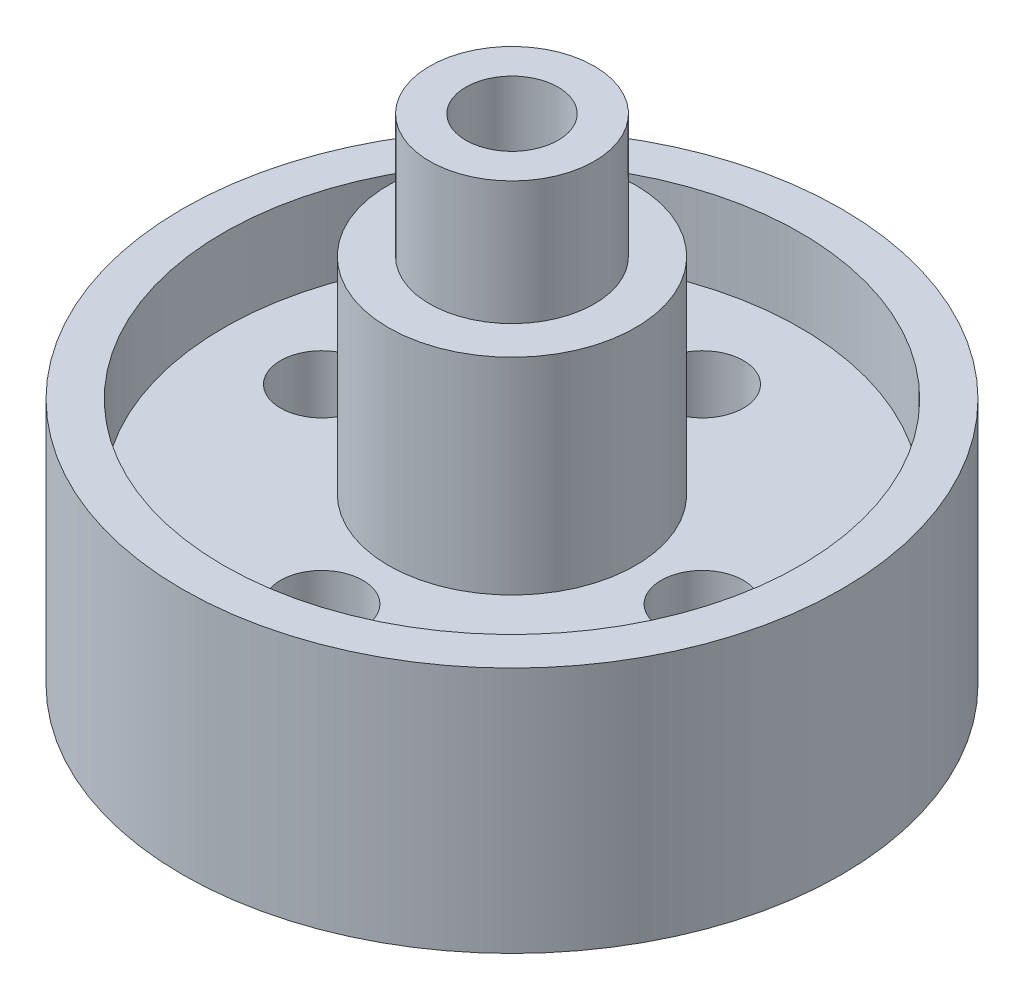
SolidWorks part; units mm, degrees
ref_plane "Front Plane" through (0, 0, 0) normal (0, 0, 1) x (1, 0, 0)
ref_plane "Top Plane" through (0, 0, 0) normal (0, 1, 0) x (1, 0, 0)
ref_plane "Right Plane" through (0, 0, 0) normal (1, 0, 0) x (0, 0, -1)
sketch "Sketch1" plane through (0, 0, 0) normal (0, 1, 0) x (1, 0, 0)
  circle A0 centre (0, 0) radius 50.8
  dimension "D1" = 101.6
extrude "Boss-Extrude1" add sketch "Sketch1" along normal blind 25.4
sketch "Sketch2" plane through (0, 25.4, 0) normal (0, 1, 0) x (1, 0, 0)
  circle A0 centre (-29.337, 0) radius 6.35
  circle A1 centre (0, 29.337) radius 6.35
  circle A2 centre (29.337, 0) radius 6.35
  circle A3 centre (0, -29.337) radius 6.35
  point P12 (0, 0)
  dimension "D1" = 12.7
  dimension "D2" = 29.337
  dimension "D3" = 4
extrude "Cut-Extrude1" cut sketch "Sketch2" against normal blind 25.4
sketch "Sketch3" plane through (0, 25.4, 0) normal (0, 1, 0) x (1, 0, 0)
  circle A0 centre (0, 0) radius 19.05
  circle A1 centre (0, 0) radius 44.45
  circle A2 centre (0, 0) radius 50.8
  circle M5 centre (0, 0) radius 50.8
  dimension "D1" = 88.9
  dimension "D2" = 38.1
  dimension "D3" = 6.35
extrude "Boss-Extrude2" add sketch "Sketch3" along normal blind 12.7 contours A1 M5
sketch "Sketch5" plane through (0, 25.4, 0) normal (0, 1, 0) x (1, 0, 0)
  circle A0 centre (0, 0) radius 19.05
  dimension "D1" = 38.1
extrude "Boss-Extrude3" add sketch "Sketch5" along normal blind 31.75
sketch "Sketch6" plane through (0, 57.15, 0) normal (0, 1, 0) x (1, 0, 0)
  circle A0 centre (0, 0) radius 12.7
  dimension "D1" = 25.4
extrude "Boss-Extrude4" add sketch "Sketch6" along normal blind 19.05
sketch "Sketch7" plane through (0, 76.2, 0) normal (0, 1, 0) x (1, 0, 0)
  circle A0 centre (0, 0) radius 7.112
  dimension "D1" = 14.224
extrude "Cut-Extrude2" cut sketch "Sketch7" against normal through all
